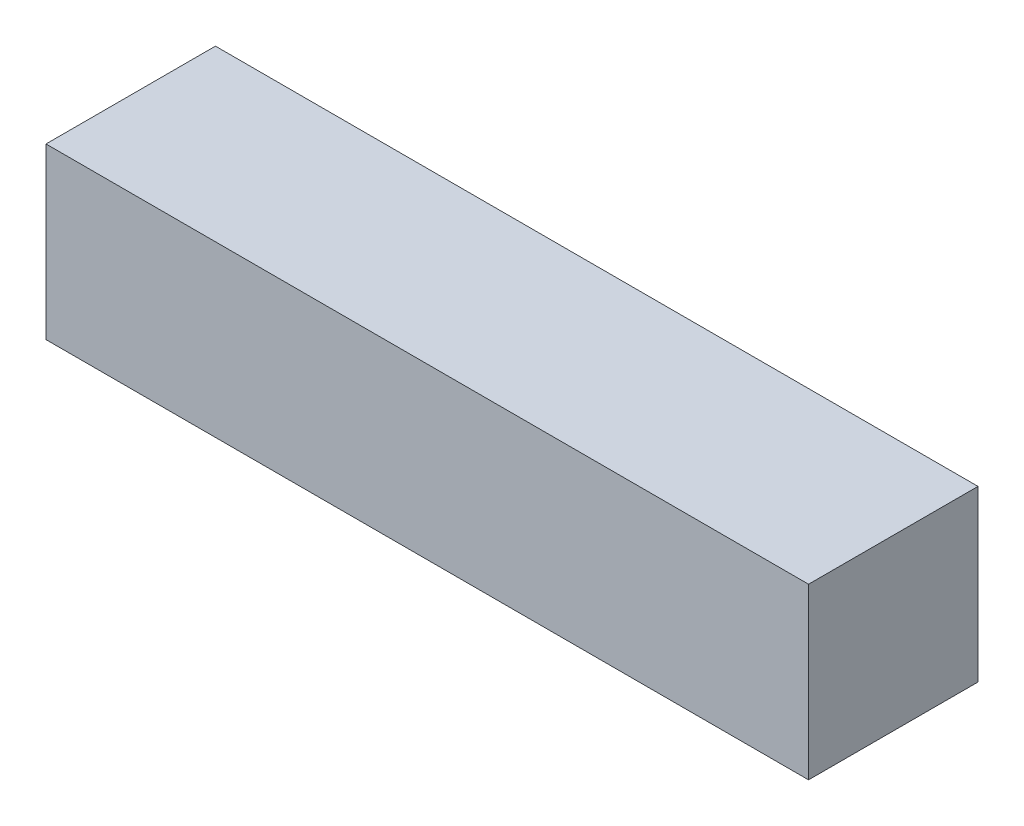
SolidWorks part; units mm, degrees
ref_plane "Alzado" through (0, 0, 0) normal (0, 0, 1) x (1, 0, 0)
ref_plane "Planta" through (0, 0, 0) normal (0, 1, 0) x (1, 0, 0)
ref_plane "Vista lateral" through (0, 0, 0) normal (1, 0, 0) x (0, 0, -1)
sketch "Croquis1" plane through (0, 0, 0) normal (1, 0, 0) x (0, 0, -1)
  line L1 (0, 0) -> (40, 0)
  line L2 (0, 0) -> (0, 40)
  line L3 (0, 40) -> (40, 40)
  line L4 (40, 0) -> (40, 40)
  dimension "D1" = 40
  dimension "D2" = 40
extrude "Saliente-Extruir1" add sketch "Croquis1" along normal blind 180
